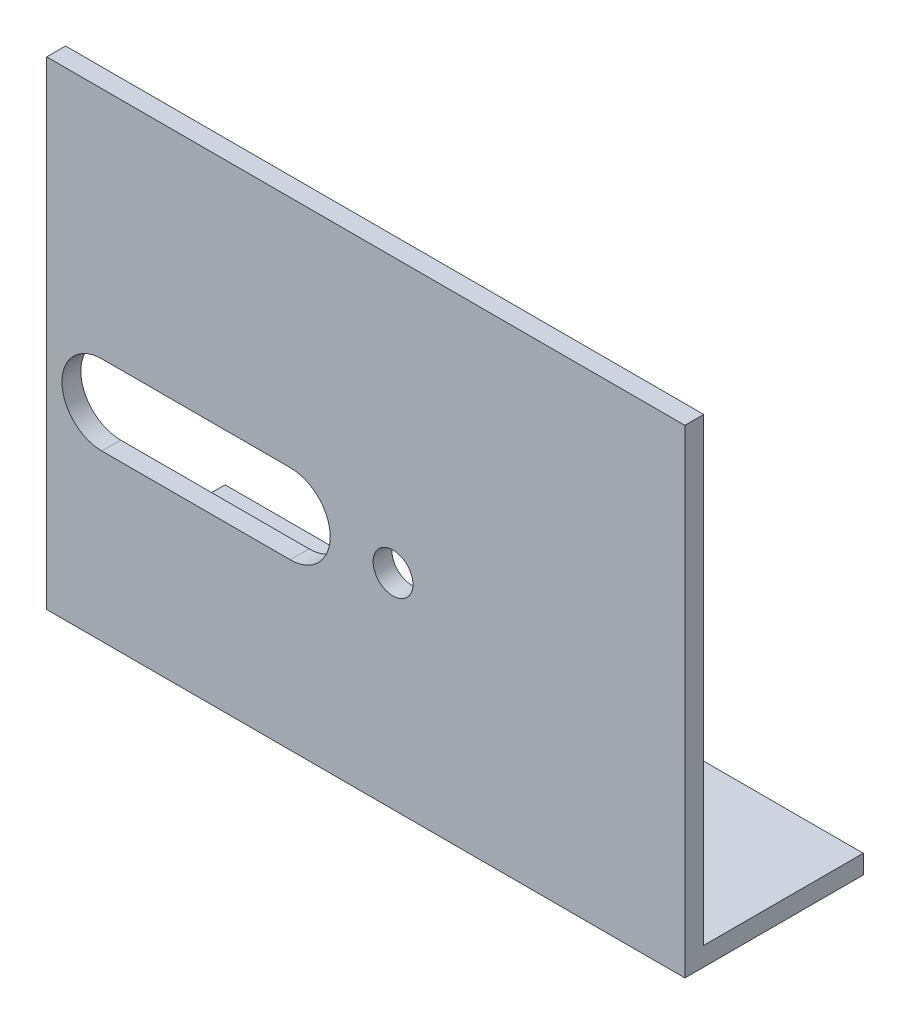
SolidWorks part; units mm, degrees
ref_plane "Alzado" through (0, 0, 0) normal (0, 0, 1) x (1, 0, 0)
ref_plane "Planta" through (0, 0, 0) normal (0, 1, 0) x (1, 0, 0)
ref_plane "Vista lateral" through (0, 0, 0) normal (1, 0, 0) x (0, 0, -1)
sketch "Croquis1" plane through (0, 0, 0) normal (0, 0, 1) x (1, 0, 0)
  line L1 (50.8, -38.1) -> (-50.8, -38.1)
  line L2 (50.8, -38.1) -> (50.8, 38.1)
  line L3 (50.8, 38.1) -> (-50.8, 38.1)
  line L4 (-50.8, -38.1) -> (-50.8, 38.1)
  line L5 (50.8, -38.1) -> (-50.8, 38.1) construction
  line L6 (50.8, 38.1) -> (-50.8, -38.1) construction
  point P0 (0, 0)
  dimension "D1" = 101.6
  dimension "D2" = 76.2
extrude "Saliente-Extruir1" add sketch "Croquis1" along normal blind 3
sketch "Croquis2" plane through (0, 0, 0) normal (0, 0, -1) x (-1, 0, 0)
  line L0 (50.8, 38.1) -> (50.8, -38.1) construction
  line L1 (-50.8, -38.1) -> (50.8, -38.1)
  line L2 (-50.8, -38.1) -> (-50.8, -35.1)
  line L3 (-50.8, -35.1) -> (50.8, -35.1)
  line L4 (50.8, -38.1) -> (50.8, -35.1)
  dimension "D1" = 3
extrude "Saliente-Extruir2" add sketch "Croquis2" along normal blind 25.4
sketch "Croquis3" plane through (0, 0, 3) normal (0, 0, 1) x (1, 0, 0)
  line L0 (-42.02, -5.5) -> (-12.02, -5.5) construction
  line L1 (-42.02, 0.85) -> (-12.02, 0.85)
  line L2 (-42.02, -11.85) -> (-12.02, -11.85)
  line L3 (-50.8, 38.1) -> (-50.8, -38.1) construction
  line L4 (-50.8, -38.1) -> (50.8, -38.1) construction
  line L5 (-5.67, -5.5) -> (4.33, -5.5) construction
  arc A0 (-42.02, 0.85) -> (-42.02, -11.85) centre (-42.02, -5.5) ccw
  arc A1 (-12.02, -11.85) -> (-12.02, 0.85) centre (-12.02, -5.5) ccw
  circle A2 centre (4.33, -5.5) radius 3.175
  point P2 (-27.02, -5.5)
  point P7 (-48.37, -5.5)
  dimension "D6" = 6.35
  dimension "D1" = 2.43
  dimension "D2" = 32.6
  dimension "D3" = 30
  dimension "D4" = 12.7
  dimension "D5" = 10
extrude "Cortar-Extruir1" cut sketch "Croquis3" against normal through all
